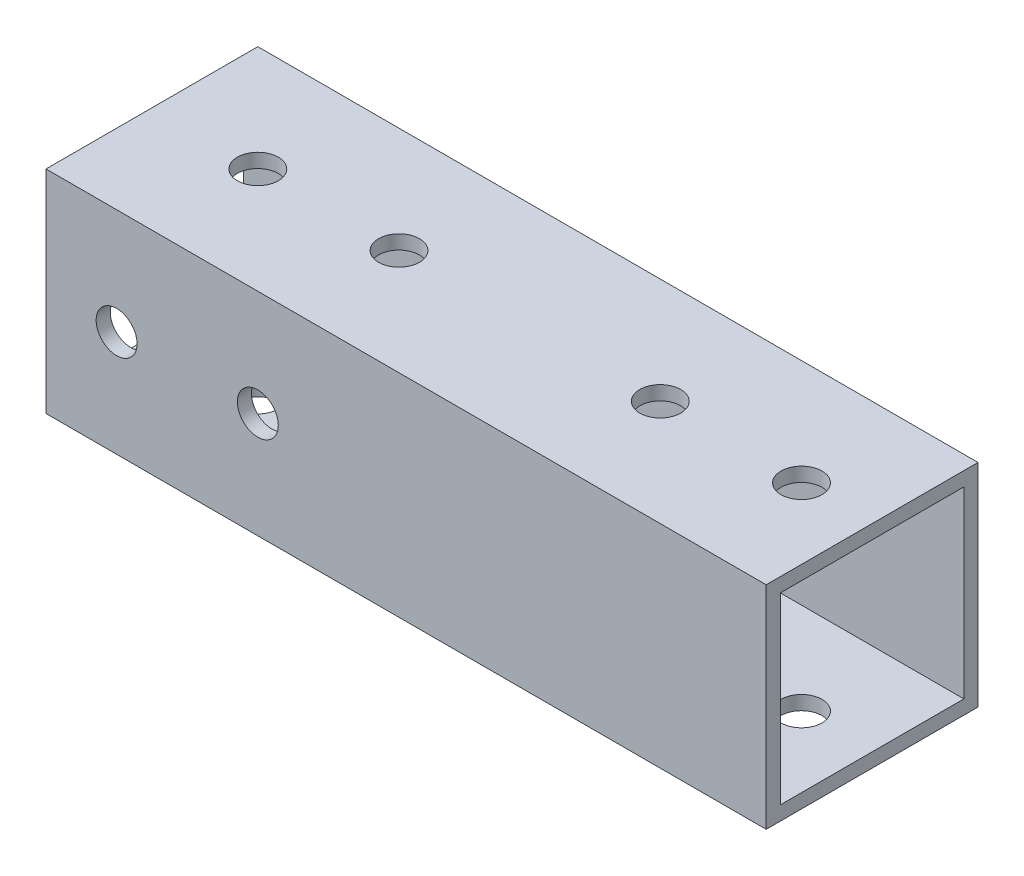
SolidWorks part; units mm, degrees
material "Thornel Mat VMA"
ref_plane "前视基准面" through (0, 0, 0) normal (0, 0, 1) x (1, 0, 0)
ref_plane "上视基准面" through (0, 0, 0) normal (0, 1, 0) x (1, 0, 0)
ref_plane "右视基准面" through (0, 0, 0) normal (1, 0, 0) x (0, 0, -1)
other "Configuration Table"
sketch "草图1" plane through (0, 0, 0) normal (1, 0, 0) x (0, 0, -1)
  line L0 (-6.5, -6.5) -> (-6.5, 6.5)
  line L1 (-7.5, -7.5) -> (7.5, -7.5)
  line L2 (-7.5, -7.5) -> (-7.5, 7.5)
  line L3 (-7.5, 7.5) -> (7.5, 7.5)
  line L4 (7.5, -7.5) -> (7.5, 7.5)
  line L5 (-7.5, -7.5) -> (7.5, 7.5) construction
  line L6 (-7.5, 7.5) -> (7.5, -7.5) construction
  line L7 (-6.5, 6.5) -> (6.5, 6.5)
  line L8 (6.5, -6.5) -> (6.5, 6.5)
  line L9 (-6.5, -6.5) -> (6.5, -6.5)
  point P0 (0, 0)
  dimension "D1" = 15
  dimension "D2" = 15
  dimension "D3" = 1
extrude "凸台-拉伸1" add sketch "草图1" along normal blind 51
sketch "草图2" plane through (0, 7.5, 0) normal (0, 1, 0) x (1, 0, 0)
  line L0 (0, 0) -> (51, 0) construction
  line L1 (51, 7.5) -> (51, -7.5) construction
  line L2 (0, 7.5) -> (0, -7.5) construction
  circle A0 centre (7.5, 0) radius 1.45
  circle A1 centre (17.5, 0) radius 1.45
  circle A3 centre (46, 0) radius 1.45
  circle A4 centre (36, 0) radius 1.45
  dimension "D1" = 2.9
  dimension "D2" = 2.9
  dimension "D3" = 2.9
  dimension "D5" = 10
  dimension "D6" = 2.9
  dimension "D8" = 10
  dimension "D4" = 7.5
  dimension "D7" = 5
extrude "切除-拉伸1" cut sketch "草图2" against normal through all
sketch "草图3" plane through (0, 0, 7.5) normal (0, 0, 1) x (1, 0, 0)
  line L0 (0, 0) -> (51, 0) construction
  line L1 (51, 7.5) -> (51, -7.5) construction
  line L2 (0, 7.5) -> (0, -7.5) construction
  circle A0 centre (5, 0) radius 1.45
  circle A1 centre (15, 0) radius 1.45
  dimension "D1" = 2.9
  dimension "D2" = 2.9
  dimension "D4" = 10
  dimension "D3" = 5
extrude "切除-拉伸2" cut sketch "草图3" against normal through all
